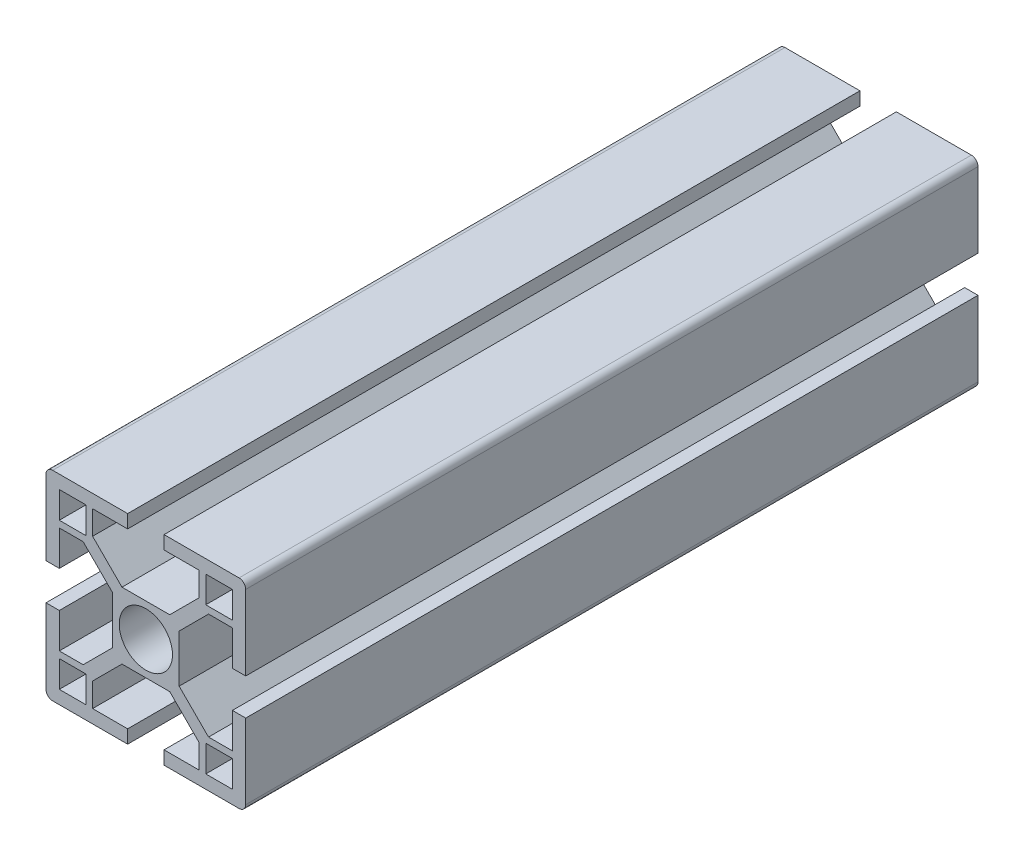
SolidWorks part; units mm, degrees
ref_plane "前视基准面" through (0, 0, 0) normal (0, 0, 1) x (1, 0, 0)
ref_plane "上视基准面" through (0, 0, 0) normal (0, 1, 0) x (1, 0, 0)
ref_plane "右视基准面" through (0, 0, 0) normal (1, 0, 0) x (0, 0, -1)
sketch "草图1" plane through (0, 0, 0) normal (0, 0, 1) x (1, 0, 0)
  line L0 (0, 0) -> (33877.4182, 0) construction
  line L1 (0, 0) -> (0, 33877.4182) construction
  line L3 (-15, 15) -> (15, 15)
  line L4 (-15, 15) -> (-15, -15)
  line L5 (-15, -15) -> (15, -15)
  line L6 (15, 15) -> (15, -15)
  dimension "D1" = 30
extrude "凸台-拉伸1" add sketch "草图1" along normal blind 110
sketch "草图2" plane through (0, 0, 110) normal (0, 0, 1) x (1, 0, 0)
  line L0 (0, 0) -> (0, 50000) construction
  line L1 (0, 0) -> (50000, 0) construction
  line L2 (0.0385, 0.0385) -> (35355.3776, 35355.3776) construction
  line L3 (-5, 5) -> (5, 5)
  line L4 (-5, 5) -> (-5, -5)
  line L5 (-5, -5) -> (5, -5)
  line L6 (5, 5) -> (5, -5)
  line L7 (-13, -13) -> (-13, -9)
  line L8 (-13, -9) -> (-9, -9)
  line L9 (-9, -9) -> (-9, -13)
  line L10 (-9, -13) -> (-13, -13)
  line L11 (-15, 15) -> (-15, -15) construction
  line L12 (-8, -9.4142) -> (-8, -13)
  line L13 (9, -9) -> (9, -13)
  line L14 (13, -9) -> (9, -9)
  line L15 (13, -13) -> (13, -9)
  line L16 (9, -13) -> (13, -13)
  line L17 (-9, 9) -> (-9, 13)
  line L18 (-13, 9) -> (-9, 9)
  line L19 (-13, 13) -> (-13, 9)
  line L20 (-9, 13) -> (-13, 13)
  line L21 (13, 9) -> (9, 9)
  line L22 (13, 13) -> (13, 9)
  line L23 (9, 13) -> (13, 13)
  line L24 (9, 9) -> (9, 13)
  line L25 (-5, -3.5858) -> (-10.4142, -9)
  line L26 (-3.5858, -5) -> (-9, -10.4142)
  line L27 (-8, -13) -> (-2.7356, -13)
  line L28 (-2.7356, -13) -> (-2.7356, -15)
  line L29 (-15, -15) -> (15, -15) construction
  line L30 (-2.7356, -15) -> (-15, -15)
  line L31 (-9.4142, -8) -> (-13, -8)
  line L32 (-13, -8) -> (-13, -2.7356)
  line L33 (-13, -2.7356) -> (-15, -2.7356)
  line L34 (-15, -2.7356) -> (-15, -15)
  line L35 (0, 0) -> (35355.3391, -35355.3391) construction
  line L36 (-5, 3.5858) -> (-10.4142, 9)
  line L37 (-3.5858, 5) -> (-9, 10.4142)
  line L38 (-2.7356, 15) -> (-15, 15)
  line L39 (-2.7356, 13) -> (-2.7356, 15)
  line L40 (-8, 13) -> (-2.7356, 13)
  line L41 (-8, 9.4142) -> (-8, 13)
  line L42 (-9.4142, 8) -> (-13, 8)
  line L43 (-13, 8) -> (-13, 2.7356)
  line L44 (-15, 2.7356) -> (-15, 15)
  line L45 (-13, 2.7356) -> (-15, 2.7356)
  line L46 (-15, 2.7356) -> (-15, -2.7356)
  line L47 (5, -3.5858) -> (10.4142, -9)
  line L48 (3.5858, -5) -> (9, -10.4142)
  line L49 (15, -2.7356) -> (15, -15)
  line L50 (2.7356, -15) -> (15, -15)
  line L51 (2.7356, -13) -> (2.7356, -15)
  line L52 (8, -13) -> (2.7356, -13)
  line L53 (8, -9.4142) -> (8, -13)
  line L54 (9.4142, -8) -> (13, -8)
  line L55 (13, -8) -> (13, -2.7356)
  line L56 (13, -2.7356) -> (15, -2.7356)
  line L57 (15, 2.7356) -> (15, -2.7356)
  line L58 (2.7356, 15) -> (15, 15)
  line L59 (15, 2.7356) -> (15, 15)
  line L60 (13, 2.7356) -> (15, 2.7356)
  line L61 (13, 8) -> (13, 2.7356)
  line L62 (9.4142, 8) -> (13, 8)
  line L63 (5, 3.5858) -> (10.4142, 9)
  line L64 (3.5858, 5) -> (9, 10.4142)
  line L65 (8, 9.4142) -> (8, 13)
  line L66 (8, 13) -> (2.7356, 13)
  line L67 (2.7356, 13) -> (2.7356, 15)
  circle A0 centre (0, 0) radius 4
  line M42 (-15, 15) -> (-15, -15)
  line M43 (-15, -15) -> (15, -15)
  line M44 (15, -15) -> (15, 15)
  line M45 (15, 15) -> (-15, 15)
  dimension "D1" = 2
  dimension "D2" = 2
  dimension "D3" = 1
  dimension "D4" = 2
extrude "切除-拉伸1" cut sketch "草图2" against normal through all contours A0 | L66 L67 L39 L40 L41 L37 L3 L64 L65 M45 | L43 L45 L33 L32 L31 L25 L4 L36 L42 M42 | L53 L48 L5 L26 L12 L27 L28 L51 L52 M43 | L63 L6 L47 L54 L55 L56 L60 L61 L62 M44 | L17 L20 L19 L18 | L24 L21 L22 L23 | L13 L16 L15 L14 | L10 L9 L8 L7
fillet "圆角2" radius 1 4 edges at (-15, 15, 55) (15, 15, 55) (15, -15, 55) (-15, -15, 55)
